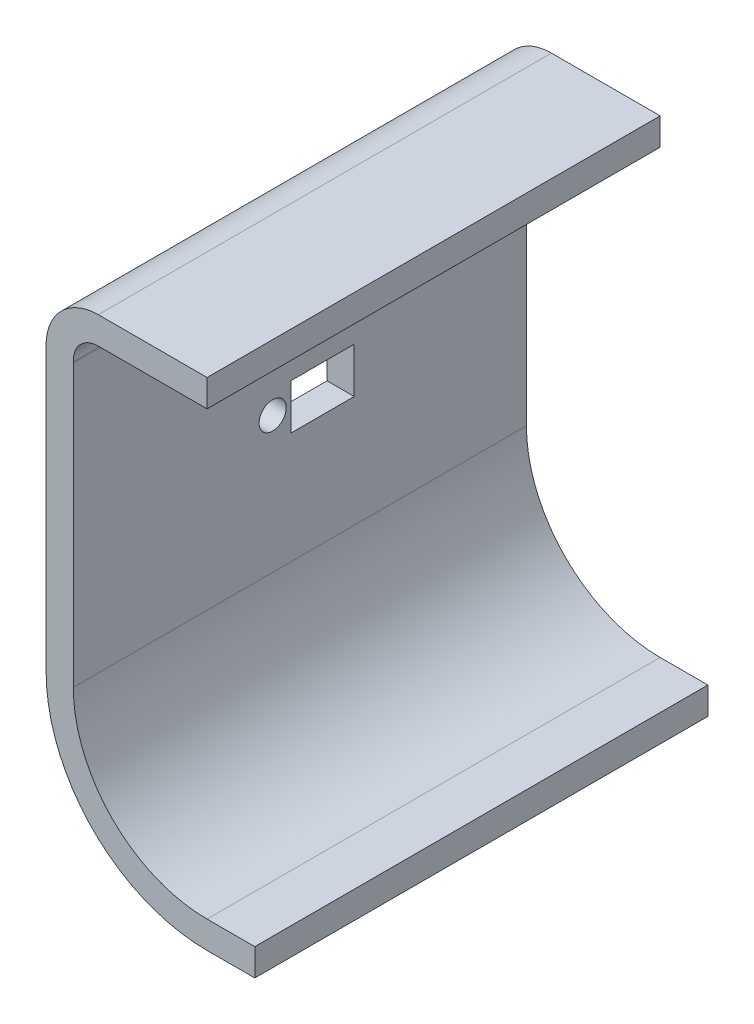
SolidWorks part; units mm, degrees
ref_plane "Front Plane" through (0, 0, 0) normal (0, 0, 1) x (1, 0, 0)
ref_plane "Top Plane" through (0, 0, 0) normal (0, 1, 0) x (1, 0, 0)
ref_plane "Right Plane" through (0, 0, 0) normal (1, 0, 0) x (0, 0, -1)
sketch "Sketch4" plane through (0, 0, 0) normal (0, 0, 1) x (1, 0, 0)
  line L0 (4.2601, 21.5) -> (16.2601, 21.5)
  line L1 (1.4975, 15.6224) -> (1.5, 15.5)
  line L2 (1.5, -15.5) -> (1.5, 15.5)
  line L4 (-1.5, -15.5) -> (-1.5, 15.5)
  line L5 (1.5, -15.5) -> (-1.5, 15.5) construction
  line L6 (1.5, 15.5) -> (-1.5, -15.5) construction
  line L7 (16.2601, 21.5) -> (16.2601, 18.5)
  line L8 (16.2601, 18.5) -> (4.2601, 18.5)
  line L10 (16.2601, -30.2601) -> (21.5252, -30.2601)
  line L11 (21.5252, -30.2601) -> (21.5252, -33.2601)
  line L12 (21.5252, -33.2601) -> (16.2601, -33.2601)
  arc A0 (-1.5, 15.5) -> (4.2601, 21.5) centre (4.2601, 15.7351) cw
  arc A1 (1.4975, 15.6224) -> (4.2601, 18.5) centre (4.2601, 15.7351) cw
  arc A2 (1.5, -15.5) -> (16.2601, -30.2601) centre (16.2601, -15.5) ccw
  arc A3 (-1.5, -15.5) -> (16.2601, -33.2601) centre (16.2601, -15.5) ccw
  point P0 (0, 0)
  dimension "D1" = 3
  dimension "D4" = 3
  dimension "D5" = 12
  dimension "D6" = 51.7601
  dimension "D7" = 3
  dimension "D8" = 37
  dimension "D9" = 23.0252
  dimension "D10" = 17.7601
  dimension "D3" = 3
extrude "Boss-Extrude4" add sketch "Sketch4" along normal blind 50 contours L4 A3 L12 L11 L10 A2 L2 L1 A1 L8 L7 L0 A0
sketch "Sketch5" plane through (-1.5, 0, 0) normal (-1, 0, 0) x (0, 0, 1)
  line L0 (50, 15.5) -> (0, 15.5) construction
  line L1 (0, -15.5) -> (0, 15.5) construction
  line L2 (50, -15.5) -> (50, 15.5) construction
  line L4 (26, -3.2) -> (19, -3.2)
  line L5 (26, -3.2) -> (26, 1.8)
  line L6 (26, 1.8) -> (19, 1.8)
  line L7 (19, -3.2) -> (19, 1.8)
  line L8 (26, -3.2) -> (19, 1.8) construction
  line L9 (26, 1.8) -> (19, -3.2) construction
  line L10 (32, 5.8) -> (20, 5.8)
  line L11 (32, 5.8) -> (32, 10.8)
  line L12 (32, 10.8) -> (20, 10.8)
  line L13 (20, 5.8) -> (20, 10.8)
  line L14 (32, 5.8) -> (20, 10.8) construction
  line L15 (32, 10.8) -> (20, 5.8) construction
  circle A0 centre (28, -0.5) radius 1.5
  point P6 (22.5, -0.7)
  point P11 (26, 8.3)
  dimension "D1" = 3
  dimension "D3" = 22
  dimension "D2" = 16
  dimension "D4" = 7
  dimension "D5" = 2
  dimension "D6" = 5
  dimension "D7" = 2.3
  dimension "D8" = 9
  dimension "D9" = 5
  dimension "D10" = 12
  dimension "D11" = 20
extrude "Cut-Extrude1" cut sketch "Sketch5" against normal through all
